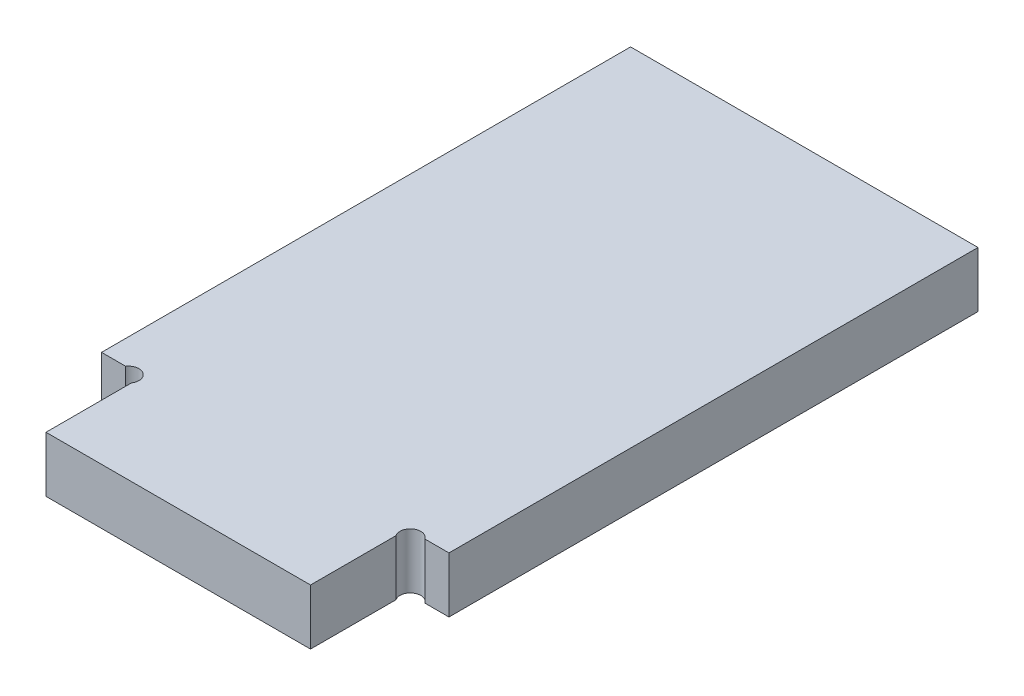
SolidWorks part; units mm, degrees
ref_plane "Front Plane" through (0, 0, 0) normal (0, 0, 1) x (1, 0, 0)
ref_plane "Top Plane" through (0, 0, 0) normal (0, 1, 0) x (1, 0, 0)
ref_plane "Right Plane" through (0, 0, 0) normal (1, 0, 0) x (0, 0, -1)
sketch "Sketch1" plane through (0, 0, 0) normal (0, 1, 0) x (1, 0, 0)
  line L0 (-1.905, -0.167) -> (-1.905, -1.397)
  line L1 (-1.905, -1.397) -> (1.905, -1.397)
  line L3 (-2.1542, 0) -> (-2.5019, 0)
  line L4 (-2.5019, 0) -> (-2.5019, 7.62)
  line L5 (-2.5019, 7.62) -> (2.5019, 7.62)
  line L6 (0, 7.62) -> (0, -1.397) construction
  line L7 (2.5019, 0) -> (2.5019, 7.62)
  line L8 (2.1542, 0) -> (2.5019, 0)
  line L9 (1.905, -0.167) -> (1.905, -1.397)
  line L10 (-1.8796, -0.0835) -> (-1.905, -0.0835) construction
  arc A0 (-1.905, -0.167) -> (-2.1542, 0) centre (-2.0296, -0.0835) ccw
  arc A1 (1.905, -0.167) -> (2.1542, 0) centre (2.0296, -0.0835) cw
  point P18 (-1.905, 0)
  dimension "D4" = 0.3
  dimension "D1" = 3.81
  dimension "D2" = 1.397
  dimension "D3" = 5.0038
  dimension "D5" = 7.62
  dimension "D6" = 0.0254
extrude "Boss-Extrude1" add sketch "Sketch1" along normal mid plane 0.8
